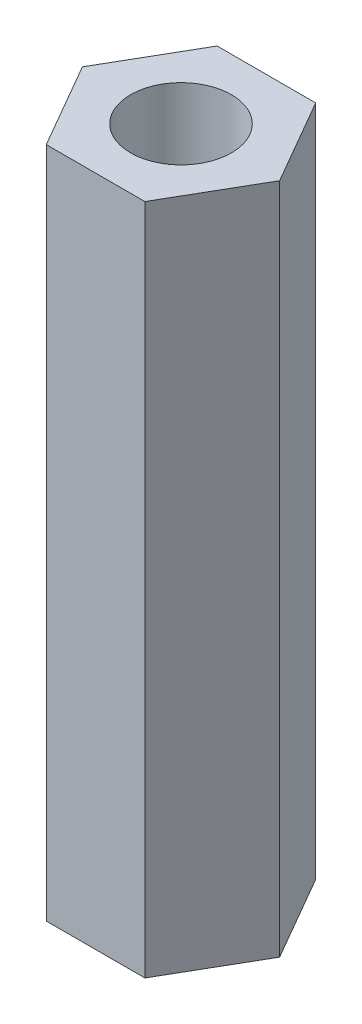
SolidWorks part; units mm, degrees
material "Nylon 101"
ref_plane "Front Plane" through (0, 0, 0) normal (0, 0, 1) x (1, 0, 0)
ref_plane "Top Plane" through (0, 0, 0) normal (0, 1, 0) x (1, 0, 0)
ref_plane "Right Plane" through (0, 0, 0) normal (1, 0, 0) x (0, 0, -1)
sketch "Sketch1" plane through (0, 0, 0) normal (0, 1, 0) x (1, 0, 0)
  line L0 (0, 0) -> (50000, 0) construction
  line L1 (0, 0) -> (0, 50000) construction
  line L2 (1.4665, 2.54) -> (-1.4665, 2.54)
  line L3 (-1.4665, 2.54) -> (-2.9329, 0)
  line L4 (1.4665, 2.54) -> (2.9329, 0)
  line L5 (1.4665, -2.54) -> (2.9329, 0)
  line L6 (-1.4665, -2.54) -> (-2.9329, 0)
  line L7 (1.4665, -2.54) -> (-1.4665, -2.54)
  circle A0 centre (0, 0) radius 1.5
  point P11 (0, 2.54)
  point P14 (0, -2.54)
  point P15 (-1.7951, 3.1605)
  point P16 (1.9986, 3.9568)
  dimension "D1" = 3
  dimension "D2" = 5.08
  dimension "D3" = 5.08
extrude "Boss-Extrude1" add sketch "Sketch1" along normal blind 20
equation "\"D3@Sketch1\"=\"D2@Sketch1\""
